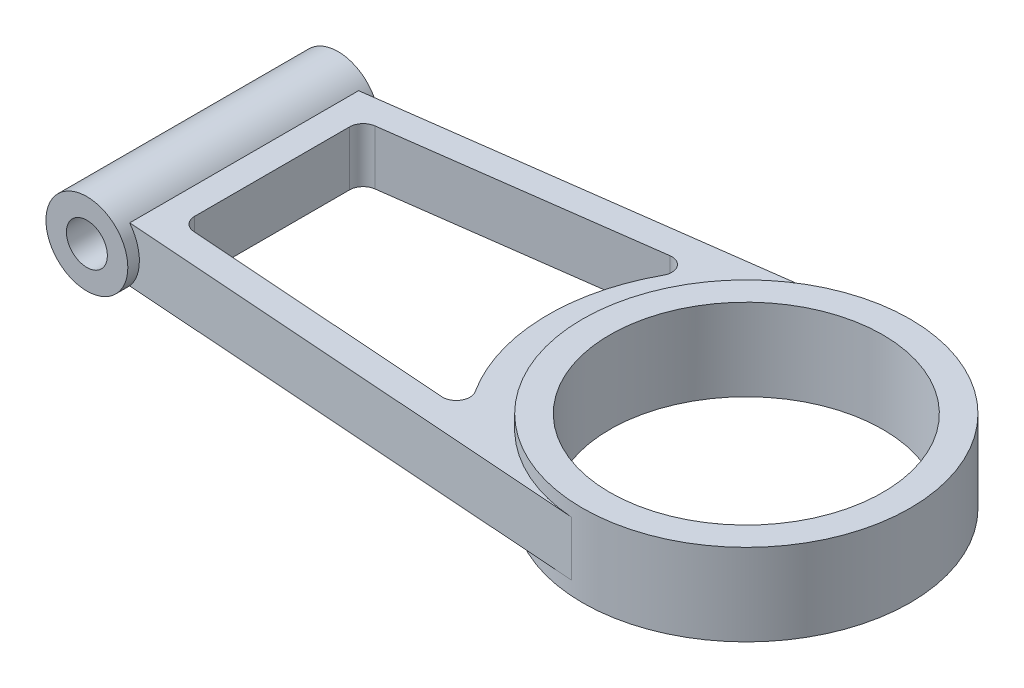
SolidWorks part; units mm, degrees
ref_plane "Front Plane" through (0, 0, 0) normal (0, 0, 1) x (1, 0, 0)
ref_plane "Top Plane" through (0, 0, 0) normal (0, 1, 0) x (1, 0, 0)
ref_plane "Right Plane" through (0, 0, 0) normal (1, 0, 0) x (0, 0, -1)
sketch "Sketch1" plane through (0, 0, 0) normal (0, 1, 0) x (1, 0, 0)
  line L1 (-60.953, 36.3178) -> (-60.953, -47.4925)
  line L2 (109.6315, 59.3709) -> (-60.953, 36.3178)
  line L3 (-60.953, -47.4925) -> (113.3954, -59.9364)
  line L4 (48.5432, 41.0244) -> (-46.6226, 28.1635)
  line L5 (-50.953, 23.2086) -> (-50.953, -33.525)
  line L6 (-46.3089, -38.5123) -> (51.4925, -45.4927)
  line L7 (115.626, 50.0901) -> (-50.953, 27.5783) construction
  line L8 (-50.953, -38.1808) -> (114.9987, -50.0254) construction
  line L9 (-50.953, 27.5783) -> (-50.953, -38.1808) construction
  line L10 (114.2868, 60) -> (-60.953, 36.3178) construction
  line L11 (-60.953, -47.4925) -> (114.2868, -60) construction
  line L12 (-72.8932, 0) -> (193.4786, 0) construction
  circle A0 centre (117.6669, -0.0886) radius 50
  arc A1 (113.3954, -59.9364) -> (109.6315, 59.3709) centre (117.6669, -0.0886) ccw
  arc A2 (53.5966, 33.6648) -> (56.0566, -37.805) centre (114.9699, 0) ccw
  arc A3 (48.5432, 41.0244) -> (53.5966, 33.6648) centre (49.2128, 36.0694) cw
  arc A4 (56.0566, -37.805) -> (51.4925, -45.4927) centre (51.8485, -40.5054) cw
  arc A5 (-50.953, -33.525) -> (-46.3089, -38.5123) centre (-45.953, -33.525) ccw
  arc A6 (-46.6226, 28.1635) -> (-50.953, 23.2086) centre (-45.953, 23.2086) ccw
  circle A7 centre (117.6669, -0.0886) radius 60
  dimension "D1" = 120
  dimension "D2" = 100
  dimension "D4" = 70
  dimension "D5" = 5
  dimension "D6" = 5
  dimension "D7" = 5
  dimension "D3" = 10
extrude "Boss-Extrude4" add sketch "Sketch1" along normal mid plane 20 contours A7 L2 L1 L3 A6 L4 A3 A2 A4 L6 A5 L5 | A1 A7 A0
sketch "Sketch4" plane through (0, 10, 0) normal (0, 1, 0) x (1, 0, 0)
  line L3 (-60.953, -47.4925) -> (113.3954, -59.9364)
  line L4 (109.6315, 59.3709) -> (-60.953, 36.3178)
  line L5 (-60.953, 36.3178) -> (-60.953, -47.4925)
  line L6 (-60.953, -47.4925) -> (113.3954, -59.9364)
  line L7 (109.6315, 59.3709) -> (-60.953, 36.3178)
  line L8 (-60.953, 36.3178) -> (-60.953, -47.4925)
  arc A1 (113.3954, -59.9364) -> (109.6315, 59.3709) centre (117.6669, -0.0886) ccw
  arc A2 (113.3954, -59.9364) -> (109.6315, 59.3709) centre (117.6669, -0.0886) ccw
  circle A3 centre (117.6669, -0.0886) radius 60
  arc M6 (113.3954, -59.9364) -> (109.6315, 59.3709) centre (117.6669, -0.0886) ccw
  circle M17 centre (117.6669, -0.0886) radius 50
  dimension "D1" = 0
extrude "Boss-Extrude5" add sketch "Sketch4" along normal blind 5 contours A3 M6 M17
sketch "Sketch5" plane through (0, -10, 0) normal (0, -1, 0) x (1, 0, 0)
  arc A0 (109.6315, -59.3709) -> (113.3954, 59.9364) centre (117.6669, 0.0886) ccw construction
  circle A1 centre (117.6669, 0.0886) radius 50 construction
  arc A2 (109.6315, -59.3709) -> (113.3954, 59.9364) centre (117.6669, 0.0886) ccw
  circle A3 centre (117.6669, 0.0886) radius 50
  circle A4 centre (117.6669, 0.0886) radius 60
  arc M4 (109.6315, -59.3709) -> (113.3954, 59.9364) centre (117.6669, 0.0886) ccw
  circle M13 centre (117.6669, 0.0886) radius 50
extrude "Boss-Extrude6" add sketch "Sketch5" along normal blind 5 contours A4 M4 M13
ref_plane "Plane2" through (0, 0, 0) normal (0, 0, 1) x (1, 0, 0)
sketch "Sketch9" plane through (0, 0, 0) normal (0, 0, 1) x (1, 0, 0)
  line L0 (-60.953, 10) -> (-60.953, -10) construction
  circle A0 centre (-71.953, 0) radius 15
  circle A1 centre (-71.953, 0) radius 7.5
  dimension "D1" = 30
  dimension "D2" = 15
  dimension "D3" = 11
extrude "Boss-Extrude8" add sketch "Sketch9" along normal mid plane 80
sketch "Sketch11" plane through (0, 0, 40) normal (0, 0, 1) x (1, 0, 0)
  circle A0 centre (-71.953, 0) radius 15
extrude "Cut-Extrude1" cut sketch "Sketch11" along normal blind 50
sketch "Sketch12" plane through (0, 0, 40) normal (0, 0, 1) x (1, 0, 0)
  circle A0 centre (-71.953, 0) radius 7.5 construction
  circle A1 centre (-71.953, 0) radius 7.5
  arc A2 (-60.7726, 10) -> (-60.7726, -10) centre (-71.953, 0) ccw
  arc A3 (-60.7726, -10) -> (-60.7726, 10) centre (-71.953, 0) ccw
  arc A4 (-60.7726, 10) -> (-60.7726, -10) centre (-71.953, 0) ccw
  arc A5 (-60.7726, -10) -> (-60.7726, 10) centre (-71.953, 0) ccw
  dimension "D1" = 0
extrude "Boss-Extrude9" add sketch "Sketch12" along normal blind 12
